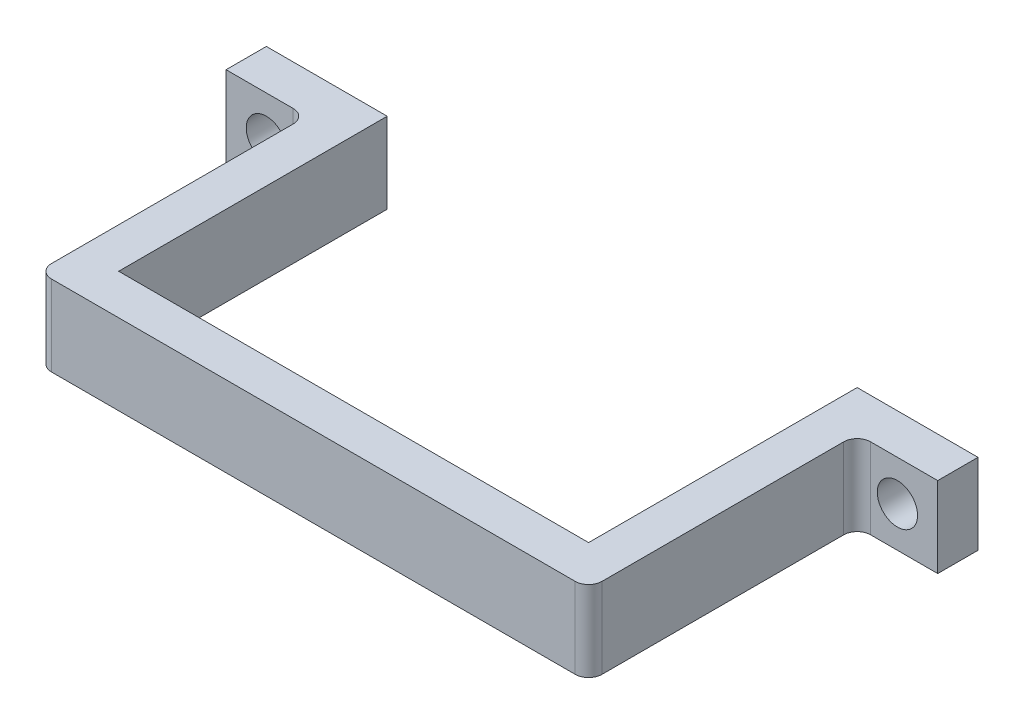
SolidWorks part; units mm, degrees
ref_plane "Front Plane" through (0, 0, 0) normal (0, 0, 1) x (1, 0, 0)
ref_plane "Top Plane" through (0, 0, 0) normal (0, 1, 0) x (1, 0, 0)
ref_plane "Right Plane" through (0, 0, 0) normal (1, 0, 0) x (0, 0, -1)
sketch "Sketch1" plane through (0, 0, 0) normal (0, 1, 0) x (1, 0, 0)
  line L1 (-19.8716, 1.9789) -> (21.1284, 1.9789)
  line L2 (-19.8716, 1.9789) -> (-19.8716, -1.0211)
  line L3 (-19.8716, -1.0211) -> (21.1284, -1.0211)
  line L4 (21.1284, 1.9789) -> (21.1284, -1.0211)
  line L5 (-19.8716, 1.9789) -> (-16.8716, 1.9789)
  line L6 (-19.8716, 1.9789) -> (-19.8716, 21.9789)
  line L7 (-19.8716, 21.9789) -> (-16.8716, 21.9789)
  line L8 (-16.8716, 1.9789) -> (-16.8716, 21.9789)
  line L9 (21.1284, 1.9789) -> (18.1284, 1.9789)
  line L10 (21.1284, 1.9789) -> (21.1284, 21.9789)
  line L11 (21.1284, 21.9789) -> (18.1284, 21.9789)
  line L12 (18.1284, 1.9789) -> (18.1284, 21.9789)
  line L13 (-19.8716, 21.9789) -> (-25.8716, 21.9789)
  line L14 (-19.8716, 21.9789) -> (-19.8716, 18.9789)
  line L15 (-19.8716, 18.9789) -> (-25.8716, 18.9789)
  line L16 (-25.8716, 21.9789) -> (-25.8716, 18.9789)
  line L17 (21.1284, 21.9789) -> (27.1284, 21.9789)
  line L18 (21.1284, 21.9789) -> (21.1284, 18.9789)
  line L19 (21.1284, 18.9789) -> (27.1284, 18.9789)
  line L20 (27.1284, 21.9789) -> (27.1284, 18.9789)
  dimension "D1" = 41
  dimension "D2" = 3
  dimension "D3" = 20
  dimension "D4" = 3
  dimension "D5" = 3
  dimension "D6" = 20
  dimension "D7" = 6
  dimension "D8" = 3
  dimension "D9" = 6
  dimension "D10" = 3
extrude "Boss-Extrude1" add sketch "Sketch1" along normal blind 6 contours L13 L16 L15 L6 | L1 L8 L7 L6 | L4 L1 L2 L3 | L12 L1 L10 L11 | L20 L17 L10 L19
sketch "Sketch2" plane through (0, 0, -18.9789) normal (0, 0, 1) x (1, 0, 0)
  line L0 (27.1284, 6) -> (27.1284, 0) construction
  line L1 (21.1284, 6) -> (27.1284, 6) construction
  line L2 (-25.8716, 6) -> (-25.8716, 0) construction
  line L3 (-19.8716, 0) -> (-25.8716, 0) construction
  circle A0 centre (-22.8716, 3) radius 1.5
  circle A1 centre (24.1284, 3) radius 1.5
  point P8 (38.7724, 7.3706)
  dimension "D1" = 3
  dimension "D2" = 3
  dimension "D3" = 3
  dimension "D4" = 3
  dimension "D5" = 3
  dimension "D6" = 3
extrude "Cut-Extrude1" cut sketch "Sketch2" against normal blind 6
fillet "Fillet1" radius 1 1 edges at (-19.8716, 3, -18.9789)
fillet "Fillet2" radius 1 1 edges at (21.1284, 3, -18.9789)
fillet "Fillet3" radius 1 1 edges at (21.1284, 3, 1.0211)
fillet "Fillet4" radius 1 1 edges at (-19.8716, 3, 1.0211)
